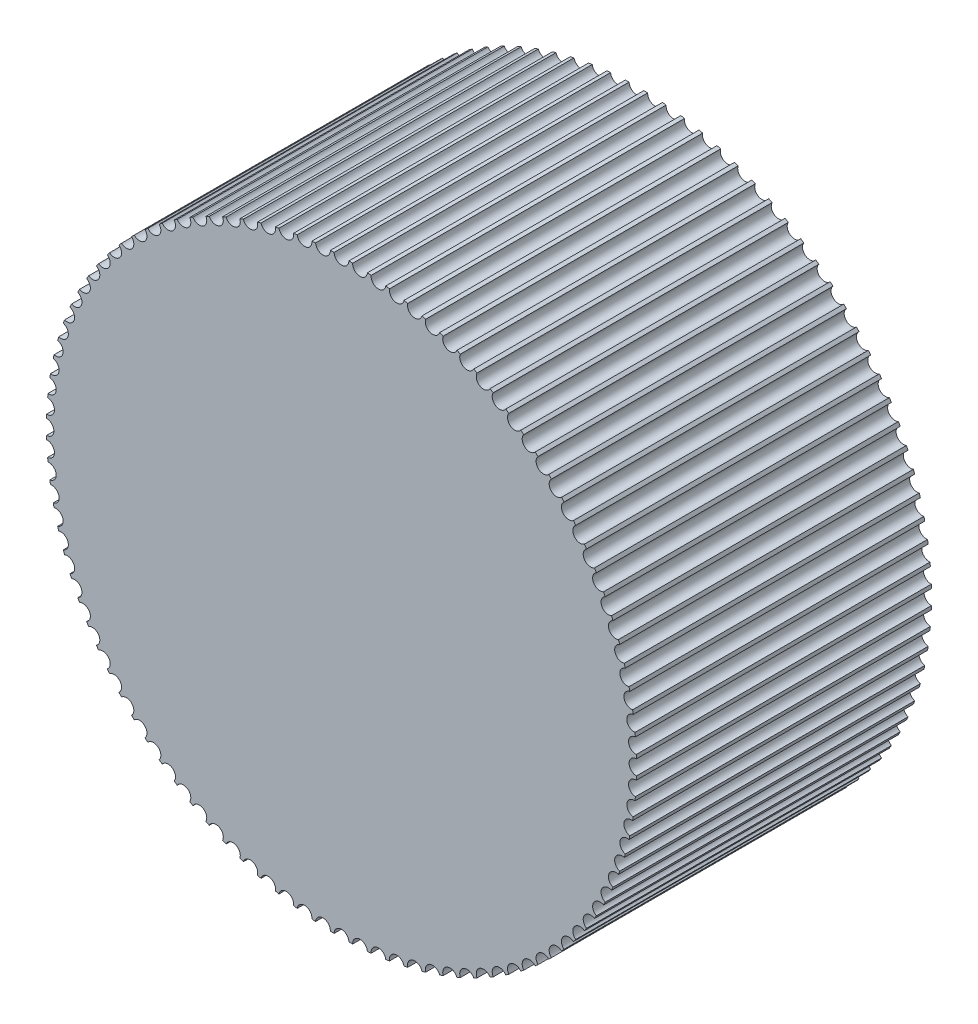
SolidWorks part; units mm, degrees
ref_plane "Front Plane" through (0, 0, 0) normal (0, 0, 1) x (1, 0, 0)
ref_plane "Top Plane" through (0, 0, 0) normal (0, 1, 0) x (1, 0, 0)
ref_plane "Right Plane" through (0, 0, 0) normal (1, 0, 0) x (0, 0, -1)
sketch "Sketch1" plane through (0, 0, 0) normal (0, 0, 1) x (1, 0, 0)
  circle A0 centre (0, 0) radius 2
extrude "Boss-Extrude1" add sketch "Sketch1" along normal blind 2
sketch "Sketch2" plane through (0, 0, 2) normal (0, 0, 1) x (1, 0, 0)
  circle A0 centre (0, 2) radius 0.05
  circle A1 centre (0, 0) radius 2 construction
  circle A2 centre (0.1256, 1.9961) radius 0.05
  circle A3 centre (0.2507, 1.9842) radius 0.05
  circle A4 centre (0.3748, 1.9646) radius 0.05
  circle A5 centre (0.4974, 1.9372) radius 0.05
  circle A6 centre (0.618, 1.9021) radius 0.05
  circle A7 centre (0.7362, 1.8596) radius 0.05
  circle A8 centre (0.8516, 1.8097) radius 0.05
  circle A9 centre (0.9635, 1.7526) radius 0.05
  circle A10 centre (1.0717, 1.6887) radius 0.05
  circle A11 centre (1.1756, 1.618) radius 0.05
  circle A12 centre (1.2748, 1.541) radius 0.05
  circle A13 centre (1.3691, 1.4579) radius 0.05
  circle A14 centre (1.4579, 1.3691) radius 0.05
  circle A15 centre (1.541, 1.2748) radius 0.05
  circle A16 centre (1.618, 1.1756) radius 0.05
  circle A17 centre (1.6887, 1.0717) radius 0.05
  circle A18 centre (1.7526, 0.9635) radius 0.05
  circle A19 centre (1.8097, 0.8516) radius 0.05
  circle A20 centre (1.8596, 0.7362) radius 0.05
  circle A21 centre (1.9021, 0.618) radius 0.05
  circle A22 centre (1.9372, 0.4974) radius 0.05
  circle A23 centre (1.9646, 0.3748) radius 0.05
  circle A24 centre (1.9842, 0.2507) radius 0.05
  circle A25 centre (1.9961, 0.1256) radius 0.05
  circle A26 centre (2, 0) radius 0.05
  circle A27 centre (1.9961, -0.1256) radius 0.05
  circle A28 centre (1.9842, -0.2507) radius 0.05
  circle A29 centre (1.9646, -0.3748) radius 0.05
  circle A30 centre (1.9372, -0.4974) radius 0.05
  circle A31 centre (1.9021, -0.618) radius 0.05
  circle A32 centre (1.8596, -0.7362) radius 0.05
  circle A33 centre (1.8097, -0.8516) radius 0.05
  circle A34 centre (1.7526, -0.9635) radius 0.05
  circle A35 centre (1.6887, -1.0717) radius 0.05
  circle A36 centre (1.618, -1.1756) radius 0.05
  circle A37 centre (1.541, -1.2748) radius 0.05
  circle A38 centre (1.4579, -1.3691) radius 0.05
  circle A39 centre (1.3691, -1.4579) radius 0.05
  circle A40 centre (1.2748, -1.541) radius 0.05
  circle A41 centre (1.1756, -1.618) radius 0.05
  circle A42 centre (1.0717, -1.6887) radius 0.05
  circle A43 centre (0.9635, -1.7526) radius 0.05
  circle A44 centre (0.8516, -1.8097) radius 0.05
  circle A45 centre (0.7362, -1.8596) radius 0.05
  circle A46 centre (0.618, -1.9021) radius 0.05
  circle A47 centre (0.4974, -1.9372) radius 0.05
  circle A48 centre (0.3748, -1.9646) radius 0.05
  circle A49 centre (0.2507, -1.9842) radius 0.05
  circle A50 centre (0.1256, -1.9961) radius 0.05
  circle A51 centre (0, -2) radius 0.05
  circle A52 centre (-0.1256, -1.9961) radius 0.05
  circle A53 centre (-0.2507, -1.9842) radius 0.05
  circle A54 centre (-0.3748, -1.9646) radius 0.05
  circle A55 centre (-0.4974, -1.9372) radius 0.05
  circle A56 centre (-0.618, -1.9021) radius 0.05
  circle A57 centre (-0.7362, -1.8596) radius 0.05
  circle A58 centre (-0.8516, -1.8097) radius 0.05
  circle A59 centre (-0.9635, -1.7526) radius 0.05
  circle A60 centre (-1.0717, -1.6887) radius 0.05
  circle A61 centre (-1.1756, -1.618) radius 0.05
  circle A62 centre (-1.2748, -1.541) radius 0.05
  circle A63 centre (-1.3691, -1.4579) radius 0.05
  circle A64 centre (-1.4579, -1.3691) radius 0.05
  circle A65 centre (-1.541, -1.2748) radius 0.05
  circle A66 centre (-1.618, -1.1756) radius 0.05
  circle A67 centre (-1.6887, -1.0717) radius 0.05
  circle A68 centre (-1.7526, -0.9635) radius 0.05
  circle A69 centre (-1.8097, -0.8516) radius 0.05
  circle A70 centre (-1.8596, -0.7362) radius 0.05
  circle A71 centre (-1.9021, -0.618) radius 0.05
  circle A72 centre (-1.9372, -0.4974) radius 0.05
  circle A73 centre (-1.9646, -0.3748) radius 0.05
  circle A74 centre (-1.9842, -0.2507) radius 0.05
  circle A75 centre (-1.9961, -0.1256) radius 0.05
  circle A76 centre (-2, 0) radius 0.05
  circle A77 centre (-1.9961, 0.1256) radius 0.05
  circle A78 centre (-1.9842, 0.2507) radius 0.05
  circle A79 centre (-1.9646, 0.3748) radius 0.05
  circle A80 centre (-1.9372, 0.4974) radius 0.05
  circle A81 centre (-1.9021, 0.618) radius 0.05
  circle A82 centre (-1.8596, 0.7362) radius 0.05
  circle A83 centre (-1.8097, 0.8516) radius 0.05
  circle A84 centre (-1.7526, 0.9635) radius 0.05
  circle A85 centre (-1.6887, 1.0717) radius 0.05
  circle A86 centre (-1.618, 1.1756) radius 0.05
  circle A87 centre (-1.541, 1.2748) radius 0.05
  circle A88 centre (-1.4579, 1.3691) radius 0.05
  circle A89 centre (-1.3691, 1.4579) radius 0.05
  circle A90 centre (-1.2748, 1.541) radius 0.05
  circle A91 centre (-1.1756, 1.618) radius 0.05
  circle A92 centre (-1.0717, 1.6887) radius 0.05
  circle A93 centre (-0.9635, 1.7526) radius 0.05
  circle A94 centre (-0.8516, 1.8097) radius 0.05
  circle A95 centre (-0.7362, 1.8596) radius 0.05
  circle A96 centre (-0.618, 1.9021) radius 0.05
  circle A97 centre (-0.4974, 1.9372) radius 0.05
  circle A98 centre (-0.3748, 1.9646) radius 0.05
  circle A99 centre (-0.2507, 1.9842) radius 0.05
  circle A100 centre (-0.1256, 1.9961) radius 0.05
  point P205 (0, 0)
  dimension "D1" = 100
extrude "Cut-Extrude4" cut sketch "Sketch2" against normal blind 3
